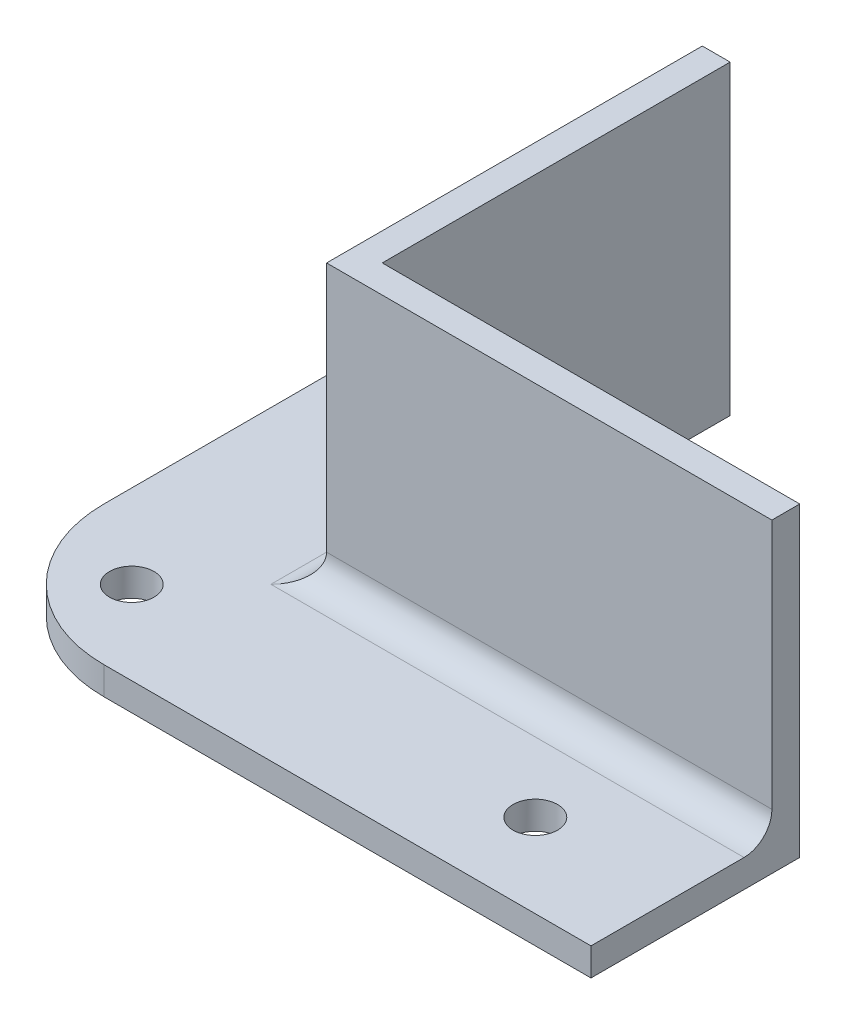
SolidWorks part; units mm, degrees
ref_plane "Front Plane" through (0, 0, 0) normal (0, 0, 1) x (1, 0, 0)
ref_plane "Top Plane" through (0, 0, 0) normal (0, 1, 0) x (1, 0, 0)
ref_plane "Right Plane" through (0, 0, 0) normal (1, 0, 0) x (0, 0, -1)
sketch "Sketch1" plane through (0, 0, 0) normal (0, 1, 0) x (1, 0, 0)
  line L0 (-23.9293, 25) -> (-8.9293, 25)
  line L1 (-8.9293, 25) -> (-8.9293, 0)
  line L2 (-8.9293, 0) -> (21.0707, 0)
  line L3 (21.0707, 0) -> (21.0707, -15)
  line L4 (21.0707, -15) -> (-23.9293, -15)
  line L5 (-23.9293, -15) -> (-23.9293, 25)
  dimension "D1" = 15
  dimension "D2" = 15
  dimension "D3" = 25
  dimension "D4" = 30
extrude "Boss-Extrude1" add sketch "Sketch1" along normal blind 2
sketch "Sketch2" plane through (0, 2, 0) normal (0, 1, 0) x (1, 0, 0)
  line L0 (-8.9293, 25) -> (-10.9293, 25)
  line L1 (-8.9293, 25) -> (-23.9293, 25) construction
  line L2 (-10.9293, 25) -> (-10.9293, -2)
  line L3 (-10.9293, -2) -> (21.0707, -2)
  line L4 (21.0707, -15) -> (21.0707, 0) construction
  line L5 (21.0707, -2) -> (21.0707, 0)
  line L6 (21.0707, 0) -> (-8.9293, 0)
  line L7 (-8.9293, 0) -> (-8.9293, 25)
  dimension "D1" = 2
  dimension "D2" = 2
extrude "Boss-Extrude2" add sketch "Sketch2" along normal blind 20
fillet "Fillet1" radius 2 2 edges at (5.0707, 2, 2) (-10.9293, 2, -11.5)
fillet "Fillet2" radius 10 1 edges at (-23.9293, 1, 15)
sketch "Sketch3" plane through (0, 2, 0) normal (0, 1, 0) x (1, 0, 0)
  line L0 (-8.9293, 0) -> (-8.9293, 25) construction
  line L1 (21.0707, 0) -> (-8.9293, 0) construction
  line L2 (-12.9293, 25) -> (-23.9293, 25) construction
  line L3 (21.0707, -15) -> (21.0707, -4) construction
  circle A0 centre (-17.9293, 15) radius 1.6
  circle A1 centre (11.0707, -9) radius 1.6
  circle A2 centre (-17.9293, -9) radius 1.6
  dimension "D1" = 3.2
  dimension "D2" = 3.2
  dimension "D3" = 3.2
  dimension "D4" = 9
  dimension "D5" = 9
  dimension "D6" = 9
  dimension "D7" = 9
  dimension "D8" = 10
  dimension "D9" = 10
extrude "Cut-Extrude1" cut sketch "Sketch3" against normal blind 20
